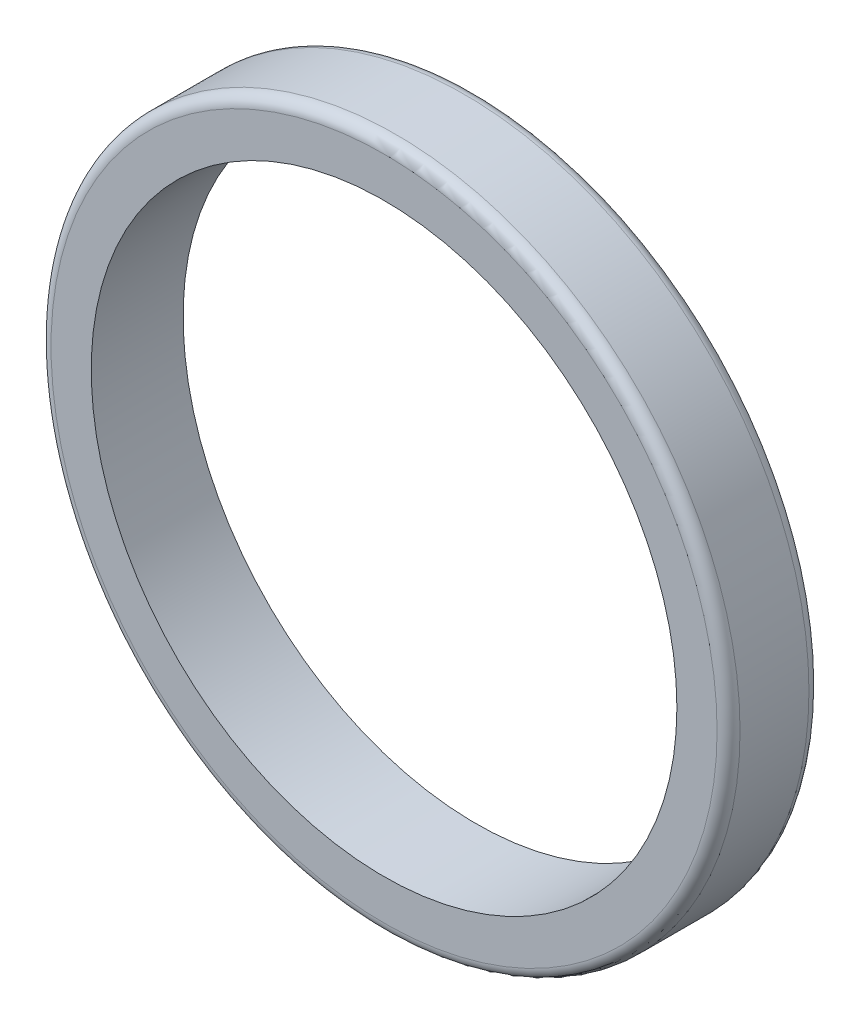
SolidWorks part; units mm, degrees
ref_plane "Plan de face" through (0, 0, 0) normal (0, 0, 1) x (1, 0, 0)
ref_plane "Plan de dessus" through (0, 0, 0) normal (0, 1, 0) x (1, 0, 0)
ref_plane "Plan de droite" through (0, 0, 0) normal (1, 0, 0) x (0, 0, -1)
sketch "Esquisse1" plane through (0, 0, 0) normal (0, 0, 1) x (1, 0, 0)
  circle A0 centre (0, 0) radius 30
  dimension "D1" = 60
extrude "Boss.-Extru.1" add sketch "Esquisse1" along normal blind 8
sketch "Esquisse2" plane through (0, 0, 8) normal (0, 0, 1) x (1, 0, 0)
  circle A0 centre (0, 0) radius 25.5
  circle A1 centre (0, 0) radius 30 construction
  dimension "D1" = 4.5
extrude "Enlèv. mat.-Extru.1" cut sketch "Esquisse2" against normal through all
fillet "Congé1" radius 1 2 edges at (30, 0, 0) (30, 0, 8)
